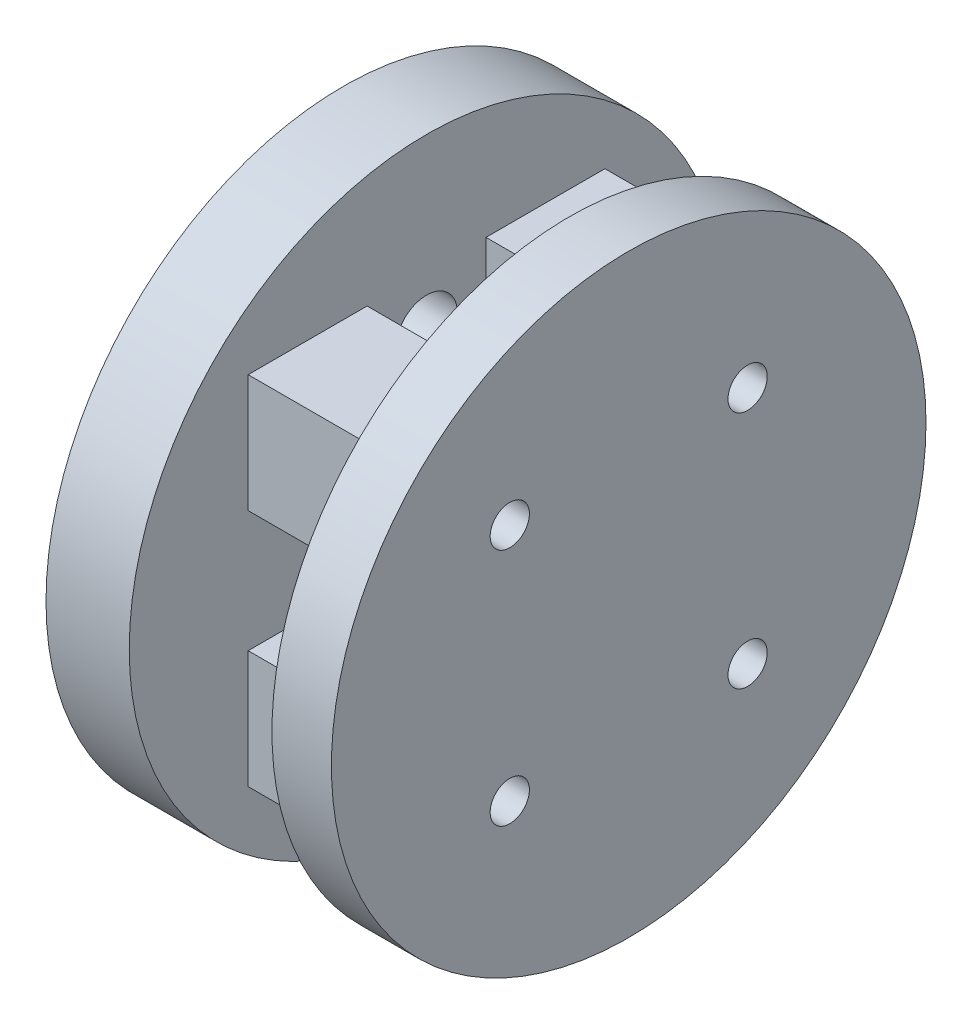
SolidWorks part; units mm, degrees
ref_plane "Front Plane" through (0, 0, 0) normal (0, 0, 1) x (1, 0, 0)
ref_plane "Top Plane" through (0, 0, 0) normal (0, 1, 0) x (1, 0, 0)
ref_plane "Right Plane" through (0, 0, 0) normal (1, 0, 0) x (0, 0, -1)
sketch "Sketch1" plane through (0, 0, 0) normal (1, 0, 0) x (0, 0, -1)
  line L1 (-15, 15) -> (15, 15)
  line L2 (-15, 15) -> (-15, -15)
  line L3 (-15, -15) -> (15, -15)
  line L4 (15, 15) -> (15, -15)
  line L5 (-15, 15) -> (15, -15) construction
  line L6 (-15, -15) -> (15, 15) construction
  point P0 (0, 0)
  dimension "D1" = 30
extrude "Boss-Extrude1" add sketch "Sketch1" along normal blind 7
sketch "Sketch2" plane through (7, 0, 0) normal (1, 0, 0) x (0, 0, -1)
  line L0 (-15, 15) -> (-15, 5.1)
  line L1 (-15, 15) -> (-15, -15) construction
  line L2 (-15, 5.1) -> (-5, 5.1)
  line L3 (-5, 5.1) -> (-5, 15)
  line L4 (15, 15) -> (-15, 15) construction
  line L5 (-5, 15) -> (-15, 15)
  line L6 (15, 15) -> (5, 15)
  line L7 (5, 15) -> (5, 5.1)
  line L8 (5, 5.1) -> (15, 5.1)
  line L9 (15, -15) -> (15, 15) construction
  line L10 (15, 5.1) -> (15, 15)
  line L11 (15, -15) -> (15, -5.1)
  line L12 (15, -5.1) -> (5, -5.1)
  line L13 (5, -5.1) -> (5, -15)
  line L14 (-15, -15) -> (15, -15) construction
  line L15 (5, -15) -> (15, -15)
  line L16 (-15, -15) -> (-5, -15)
  line L17 (-5, -15) -> (-5, -5.1)
  line L18 (-5, -5.1) -> (-15, -5.1)
  line L19 (-15, -5.1) -> (-15, -15)
  dimension "D1" = 10.2
  dimension "D2" = 10
extrude "Boss-Extrude2" add sketch "Sketch2" along normal blind 12
sketch "Sketch3" plane through (7, 0, 0) normal (1, 0, 0) x (0, 0, -1)
  line L0 (0, 10.7) -> (0, -10.7) construction
  circle A0 centre (0, 10.7) radius 2.5963
  circle A1 centre (0, -10.7) radius 2.5963
  circle A2 centre (0, 0) radius 2.5963
  point P4 (0, 0)
  dimension "D1" = 21.4
extrude "Cut-Extrude1" cut sketch "Sketch3" against normal through all
sketch "Sketch4" plane through (0, 0, 0) normal (-1, 0, 0) x (0, 0, 1)
  line L8 (-15, 15) -> (15, 15) construction
  line L9 (-15, 15) -> (15, 15)
  line L10 (15, 15) -> (15, -15) construction
  line L17 (15, -15) -> (-15, -15) construction
  line L24 (-15, -15) -> (-15, 15) construction
  line L25 (15, 15) -> (15, -15)
  line L26 (15, -15) -> (-15, -15)
  line L27 (-15, -15) -> (-15, 15)
  circle A9 centre (0, 0) radius 25
  dimension "D1" = 50
extrude "Boss-Extrude4" add sketch "Sketch4" against normal up to surface (7 mm away) up to face at (7, 10.7, -2.5963)
sketch "Sketch5" plane through (19, 0, 0) normal (1, 0, 0) x (0, 0, -1)
  circle A0 centre (0, 0) radius 25 construction
  circle A1 centre (0, 0) radius 25
extrude "Boss-Extrude5" add sketch "Sketch5" along normal blind 5 separate body
sketch "Sketch6" plane through (24, 0, 0) normal (1, 0, 0) x (0, 0, -1)
  line L0 (5, 15) -> (15, 15) construction
  line L1 (5, 15) -> (5, 5.1) construction
  line L2 (-15, 15) -> (-5, 15) construction
  line L3 (-15, 5.1) -> (-15, 15) construction
  line L4 (5, -5.1) -> (5, -15) construction
  line L5 (15, -5.1) -> (5, -5.1) construction
  line L6 (-5, -5.1) -> (-15, -5.1) construction
  line L7 (-15, -15) -> (-15, -5.1) construction
  line L8 (5, 15) -> (15, 15) construction
  line L9 (5, 15) -> (5, 5.1) construction
  line L10 (-15, 15) -> (-5, 15) construction
  line L11 (-15, 5.1) -> (-15, 15) construction
  line L12 (5, -5.1) -> (5, -15) construction
  line L13 (15, -5.1) -> (5, -5.1) construction
  line L14 (-5, -5.1) -> (-15, -5.1) construction
  line L15 (-15, -15) -> (-15, -5.1) construction
  line L16 (-15, 5.1) -> (-5, 15) construction
  line L17 (-15, -15) -> (-5, -5.1) construction
  line L18 (5, -15) -> (15, -5.1) construction
  line L19 (5, 5.1) -> (15, 15) construction
  circle A1 centre (-10, 10.05) radius 1.45
  circle A2 centre (-10, -10.05) radius 1.45
  circle A3 centre (10, -10.05) radius 1.45
  circle A4 centre (10, 10.05) radius 1.45
  dimension "D1" = 2.9
extrude "Cut-Extrude2" cut sketch "Sketch6" against normal blind 10
sketch "Sketch7" plane through (24, 0, 0) normal (1, 0, 0) x (0, 0, -1)
  circle A0 centre (10, 10.05) radius 1.45 construction
  circle A1 centre (10, -10.05) radius 1.45 construction
  circle A2 centre (-10, -10.05) radius 1.45 construction
  circle A3 centre (-10, 10.05) radius 1.45 construction
  circle A4 centre (10, 10.05) radius 1.45 construction
  circle A5 centre (10, -10.05) radius 1.45 construction
  circle A6 centre (-10, -10.05) radius 1.45 construction
  circle A7 centre (-10, 10.05) radius 1.45 construction
  circle A8 centre (-10, 10.05) radius 1.65
  circle A9 centre (-10, -10.05) radius 1.65
  circle A10 centre (10, -10.05) radius 1.65
  circle A11 centre (10, 10.05) radius 1.65
  dimension "D1" = 3.3
extrude "Cut-Extrude3" cut sketch "Sketch7" against normal through all
